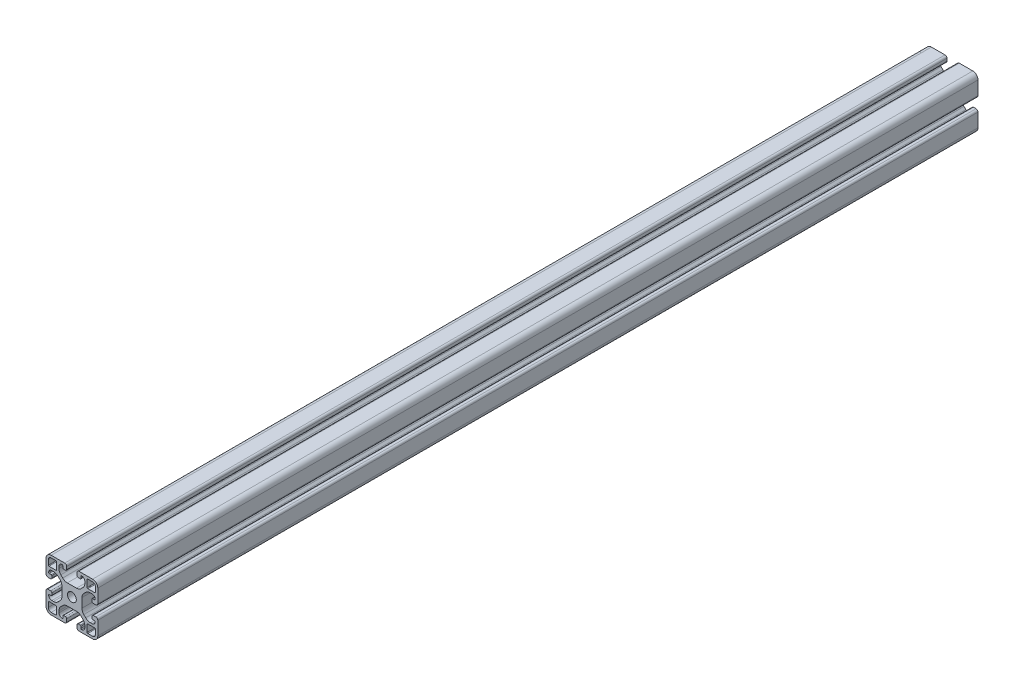
SolidWorks part; units mm, degrees
ref_plane "Plan de face" through (0, 0, 0) normal (0, 0, 1) x (1, 0, 0)
ref_plane "Plan de dessus" through (0, 0, 0) normal (0, 1, 0) x (1, 0, 0)
ref_plane "Plan de droite" through (0, 0, 0) normal (1, 0, 0) x (0, 0, -1)
ref_plane "Plan1" through (0, 0, -30) normal (0, 0, -1) x (-1, 0, 0)
sketch "Esquisse1" plane through (0, 0, -30) normal (0, 0, -1) x (-1, 0, 0)
  line L0 (-4.5, 15) -> (-4.5, 13.5)
  line L1 (-4, 13) -> (-2.5, 13)
  line L2 (-4.5, 10) -> (-5.8076, 10)
  line L3 (-9.3431, 11.4645) -> (-10.7855, 12.9069)
  line L4 (-12.25, 16.4424) -> (-12.25, 23.5576)
  line L5 (-10.7855, 27.0931) -> (-9.3431, 28.5355)
  line L6 (-5.8076, 30) -> (-4.5, 30)
  line L7 (-2.5, 27) -> (-4, 27)
  line L8 (-4.5, 26.5) -> (-4.5, 25)
  line L9 (-3.5, 24) -> (-1.5, 24)
  line L10 (0, 25.5) -> (0, 36)
  line L11 (-4, 40) -> (-14.5, 40)
  line L12 (-16, 38.5) -> (-16, 36.5)
  line L13 (-15, 35.5) -> (-13.5, 35.5)
  line L14 (-13, 36) -> (-13, 37.5)
  line L15 (-10, 35.5) -> (-10, 34.1924)
  line L16 (-11.4645, 30.6569) -> (-12.9069, 29.2145)
  line L17 (-16.4424, 27.75) -> (-23.5576, 27.75)
  line L18 (-27.0931, 29.2145) -> (-28.5355, 30.6569)
  line L19 (-30, 34.1924) -> (-30, 35.5)
  line L20 (-27, 37.5) -> (-27, 36)
  line L21 (-26.5, 35.5) -> (-25, 35.5)
  line L22 (-24, 36.5) -> (-24, 38.5)
  line L23 (-25.5, 40) -> (-36, 40)
  line L24 (-40, 36) -> (-40, 25.5)
  line L25 (-38.5, 24) -> (-36.5, 24)
  line L26 (-35.5, 25) -> (-35.5, 26.5)
  line L27 (-36, 27) -> (-37.5, 27)
  line L28 (-35.5, 30) -> (-34.1924, 30)
  line L29 (-30.6569, 28.5355) -> (-29.2145, 27.0931)
  line L30 (-27.75, 23.5576) -> (-27.75, 16.4424)
  line L31 (-29.2145, 12.9069) -> (-30.6569, 11.4645)
  line L32 (-34.1924, 10) -> (-35.5, 10)
  line L33 (-37.5, 13) -> (-36, 13)
  line L34 (-35.5, 13.5) -> (-35.5, 15)
  line L35 (-36.5, 16) -> (-38.5, 16)
  line L36 (-40, 14.5) -> (-40, 4)
  line L37 (-36, 0) -> (-25.5, 0)
  line L38 (-24, 1.5) -> (-24, 3.5)
  line L39 (-25, 4.5) -> (-26.5, 4.5)
  line L40 (-27, 4) -> (-27, 2.5)
  line L41 (-30, 4.5) -> (-30, 5.8076)
  line L42 (-28.5355, 9.3431) -> (-27.0931, 10.7855)
  line L43 (-23.5576, 12.25) -> (-16.4424, 12.25)
  line L44 (-12.9069, 10.7855) -> (-11.4645, 9.3431)
  line L45 (-10, 5.8076) -> (-10, 4.5)
  line L46 (-13, 2.5) -> (-13, 4)
  line L47 (-13.5, 4.5) -> (-15, 4.5)
  line L48 (-16, 3.5) -> (-16, 1.5)
  line L49 (-14.5, 0) -> (-4, 0)
  line L50 (0, 4) -> (0, 14.5)
  line L51 (-1.5, 16) -> (-3.5, 16)
  line L52 (-4, 1.8) -> (-7.7, 1.8)
  line L53 (-8.2, 2.3) -> (-8.2, 7.7)
  line L54 (-7.7, 8.2) -> (-2.3, 8.2)
  line L55 (-1.8, 7.7) -> (-1.8, 4)
  line L56 (-38.2, 4) -> (-38.2, 7.7)
  line L57 (-37.7, 8.2) -> (-32.3, 8.2)
  line L58 (-31.8, 7.7) -> (-31.8, 2.3)
  line L59 (-32.3, 1.8) -> (-36, 1.8)
  line L60 (-36, 38.2) -> (-32.3, 38.2)
  line L61 (-31.8, 37.7) -> (-31.8, 32.3)
  line L62 (-32.3, 31.8) -> (-37.7, 31.8)
  line L63 (-38.2, 32.3) -> (-38.2, 36)
  line L64 (-1.8, 36) -> (-1.8, 32.3)
  line L65 (-2.3, 31.8) -> (-7.7, 31.8)
  line L66 (-8.2, 32.3) -> (-8.2, 37.7)
  line L67 (-7.7, 38.2) -> (-4, 38.2)
  arc A0 (-4.5, 13.5) -> (-4, 13) centre (-4, 13.5) ccw
  arc A1 (-2.5, 13) -> (-2, 12.5) centre (-2.5, 12.5) cw
  arc A2 (-2, 12.5) -> (-4.5, 10) centre (-4.5, 12.5) cw
  arc A3 (-5.8076, 10) -> (-9.3431, 11.4645) centre (-5.8076, 15) cw
  arc A4 (-10.7855, 12.9069) -> (-12.25, 16.4424) centre (-7.25, 16.4424) cw
  arc A5 (-12.25, 23.5576) -> (-10.7855, 27.0931) centre (-7.25, 23.5576) cw
  arc A6 (-9.3431, 28.5355) -> (-5.8076, 30) centre (-5.8076, 25) cw
  arc A7 (-4.5, 30) -> (-2, 27.5) centre (-4.5, 27.5) cw
  arc A8 (-2, 27.5) -> (-2.5, 27) centre (-2.5, 27.5) cw
  arc A9 (-4, 27) -> (-4.5, 26.5) centre (-4, 26.5) ccw
  arc A10 (-4.5, 25) -> (-3.5, 24) centre (-3.5, 25) ccw
  arc A11 (-1.5, 24) -> (0, 25.5) centre (-1.5, 25.5) ccw
  arc A12 (0, 36) -> (-4, 40) centre (-4, 36) ccw
  arc A13 (-14.5, 40) -> (-16, 38.5) centre (-14.5, 38.5) ccw
  arc A14 (-16, 36.5) -> (-15, 35.5) centre (-15, 36.5) ccw
  arc A15 (-13.5, 35.5) -> (-13, 36) centre (-13.5, 36) ccw
  arc A16 (-13, 37.5) -> (-12.5, 38) centre (-12.5, 37.5) cw
  arc A17 (-12.5, 38) -> (-10, 35.5) centre (-12.5, 35.5) cw
  arc A18 (-10, 34.1924) -> (-11.4645, 30.6569) centre (-15, 34.1924) cw
  arc A19 (-12.9069, 29.2145) -> (-16.4424, 27.75) centre (-16.4424, 32.75) cw
  arc A20 (-23.5576, 27.75) -> (-27.0931, 29.2145) centre (-23.5576, 32.75) cw
  arc A21 (-28.5355, 30.6569) -> (-30, 34.1924) centre (-25, 34.1924) cw
  arc A22 (-30, 35.5) -> (-27.5, 38) centre (-27.5, 35.5) cw
  arc A23 (-27.5, 38) -> (-27, 37.5) centre (-27.5, 37.5) cw
  arc A24 (-27, 36) -> (-26.5, 35.5) centre (-26.5, 36) ccw
  arc A25 (-25, 35.5) -> (-24, 36.5) centre (-25, 36.5) ccw
  arc A26 (-24, 38.5) -> (-25.5, 40) centre (-25.5, 38.5) ccw
  arc A27 (-36, 40) -> (-40, 36) centre (-36, 36) ccw
  arc A28 (-40, 25.5) -> (-38.5, 24) centre (-38.5, 25.5) ccw
  arc A29 (-36.5, 24) -> (-35.5, 25) centre (-36.5, 25) ccw
  arc A30 (-35.5, 26.5) -> (-36, 27) centre (-36, 26.5) ccw
  arc A31 (-37.5, 27) -> (-38, 27.5) centre (-37.5, 27.5) cw
  arc A32 (-38, 27.5) -> (-35.5, 30) centre (-35.5, 27.5) cw
  arc A33 (-34.1924, 30) -> (-30.6569, 28.5355) centre (-34.1924, 25) cw
  arc A34 (-29.2145, 27.0931) -> (-27.75, 23.5576) centre (-32.75, 23.5576) cw
  arc A35 (-27.75, 16.4424) -> (-29.2145, 12.9069) centre (-32.75, 16.4424) cw
  arc A36 (-30.6569, 11.4645) -> (-34.1924, 10) centre (-34.1924, 15) cw
  arc A37 (-35.5, 10) -> (-38, 12.5) centre (-35.5, 12.5) cw
  arc A38 (-38, 12.5) -> (-37.5, 13) centre (-37.5, 12.5) cw
  arc A39 (-36, 13) -> (-35.5, 13.5) centre (-36, 13.5) ccw
  arc A40 (-35.5, 15) -> (-36.5, 16) centre (-36.5, 15) ccw
  arc A41 (-38.5, 16) -> (-40, 14.5) centre (-38.5, 14.5) ccw
  arc A42 (-40, 4) -> (-36, 0) centre (-36, 4) ccw
  arc A43 (-25.5, 0) -> (-24, 1.5) centre (-25.5, 1.5) ccw
  arc A44 (-24, 3.5) -> (-25, 4.5) centre (-25, 3.5) ccw
  arc A45 (-26.5, 4.5) -> (-27, 4) centre (-26.5, 4) ccw
  arc A46 (-27, 2.5) -> (-27.5, 2) centre (-27.5, 2.5) cw
  arc A47 (-27.5, 2) -> (-30, 4.5) centre (-27.5, 4.5) cw
  arc A48 (-30, 5.8076) -> (-28.5355, 9.3431) centre (-25, 5.8076) cw
  arc A49 (-27.0931, 10.7855) -> (-23.5576, 12.25) centre (-23.5576, 7.25) cw
  arc A50 (-16.4424, 12.25) -> (-12.9069, 10.7855) centre (-16.4424, 7.25) cw
  arc A51 (-11.4645, 9.3431) -> (-10, 5.8076) centre (-15, 5.8076) cw
  arc A52 (-10, 4.5) -> (-12.5, 2) centre (-12.5, 4.5) cw
  arc A53 (-12.5, 2) -> (-13, 2.5) centre (-12.5, 2.5) cw
  arc A54 (-13, 4) -> (-13.5, 4.5) centre (-13.5, 4) ccw
  arc A55 (-15, 4.5) -> (-16, 3.5) centre (-15, 3.5) ccw
  arc A56 (-16, 1.5) -> (-14.5, 0) centre (-14.5, 1.5) ccw
  arc A57 (-4, 0) -> (0, 4) centre (-4, 4) ccw
  arc A58 (0, 14.5) -> (-1.5, 16) centre (-1.5, 14.5) ccw
  arc A59 (-3.5, 16) -> (-4.5, 15) centre (-3.5, 15) ccw
  circle A60 centre (-20, 20) radius 3.4
  arc A61 (-1.8, 4) -> (-4, 1.8) centre (-4, 4) cw
  arc A62 (-7.7, 1.8) -> (-8.2, 2.3) centre (-7.7, 2.3) cw
  arc A63 (-8.2, 7.7) -> (-7.7, 8.2) centre (-7.7, 7.7) cw
  arc A64 (-2.3, 8.2) -> (-1.8, 7.7) centre (-2.3, 7.7) cw
  arc A65 (-36, 1.8) -> (-38.2, 4) centre (-36, 4) cw
  arc A66 (-38.2, 7.7) -> (-37.7, 8.2) centre (-37.7, 7.7) cw
  arc A67 (-32.3, 8.2) -> (-31.8, 7.7) centre (-32.3, 7.7) cw
  arc A68 (-31.8, 2.3) -> (-32.3, 1.8) centre (-32.3, 2.3) cw
  arc A69 (-38.2, 36) -> (-36, 38.2) centre (-36, 36) cw
  arc A70 (-32.3, 38.2) -> (-31.8, 37.7) centre (-32.3, 37.7) cw
  arc A71 (-31.8, 32.3) -> (-32.3, 31.8) centre (-32.3, 32.3) cw
  arc A72 (-37.7, 31.8) -> (-38.2, 32.3) centre (-37.7, 32.3) cw
  arc A73 (-4, 38.2) -> (-1.8, 36) centre (-4, 36) cw
  arc A74 (-1.8, 32.3) -> (-2.3, 31.8) centre (-2.3, 32.3) cw
  arc A75 (-7.7, 31.8) -> (-8.2, 32.3) centre (-7.7, 32.3) cw
  arc A76 (-8.2, 37.7) -> (-7.7, 38.2) centre (-7.7, 37.7) cw
extrude "Boss.-Extru.1" add sketch "Esquisse1" against normal blind 680
